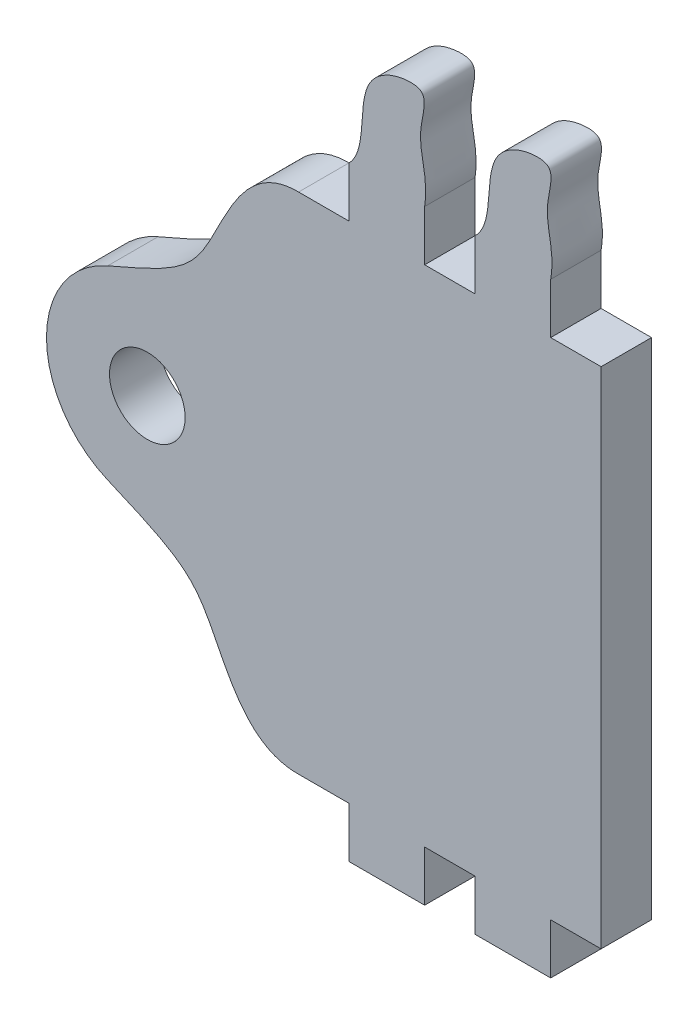
SolidWorks part; units mm, degrees
ref_plane "Front Plane" through (0, 0, 0) normal (0, 0, 1) x (1, 0, 0)
ref_plane "Top Plane" through (0, 0, 0) normal (0, 1, 0) x (1, 0, 0)
ref_plane "Right Plane" through (0, 0, 0) normal (1, 0, 0) x (0, 0, -1)
sketch "Sketch1" plane through (0, 0, 0) normal (0, 0, 1) x (1, 0, 0)
  line L0 (0, 0) -> (-3.2347, 0)
  line L1 (9.525, -15.875) -> (-9.525, -15.875)
  line L2 (9.525, -15.875) -> (9.525, 15.875)
  line L3 (9.525, 15.875) -> (-9.525, 15.875)
  line L4 (-9.525, -15.875) -> (-9.525, 15.875)
  line L5 (9.525, -15.875) -> (-9.525, 15.875) construction
  line L6 (9.525, 15.875) -> (-9.525, -15.875) construction
  line L7 (6.35, -15.875) -> (6.35, -19.05)
  line L8 (-6.35, 15.875) -> (-1.5875, 15.875)
  line L9 (-6.35, 15.875) -> (-6.35, 19.05)
  line L10 (-6.35, 19.05) -> (-1.5875, 19.05)
  line L11 (-1.5875, 15.875) -> (-1.5875, 19.05)
  line L12 (1.5875, 15.875) -> (6.35, 15.875)
  line L13 (1.5875, 15.875) -> (1.5875, 19.05)
  line L14 (1.5875, 19.05) -> (6.35, 19.05)
  line L15 (6.35, 15.875) -> (6.35, 19.05)
  line L16 (1.5875, -15.875) -> (1.5875, -19.05)
  line L17 (1.5875, -19.05) -> (6.35, -19.05)
  line L18 (-6.35, -15.875) -> (-6.35, -19.05)
  line L19 (-6.35, -19.05) -> (-1.5875, -19.05)
  line L20 (-1.5875, -15.875) -> (-1.5875, -19.05)
  circle A0 centre (-19.05, 0) radius 2.3813
  circle A1 centre (-19.05, 0) radius 6.35
  spline S0 degree 3 poles (-21.5476, 5.8382) (-17.7414, 7.4665) (-15.0309, 8.8365) (-13.0093, 15.9171) (-9.525, 15.875) knots 0 0 0 0 0.458191 1 1 1 1
  spline S1 degree 3 poles (-6.35, 19.05) (-5.1089, 20.3128) (-6.2488, 23.7826) (-3.5047, 25.4227) (-1.2706, 25.4019) (-2.3305, 22.1182) (-1.303, 20.9023) (-1.5875, 19.05) knots 0 0 0 0 0.348301 0.511854 0.587996 0.709542 1 1 1 1
  spline S2 degree 3 poles (1.5875, 19.05) (2.8761, 20.283) (1.7509, 23.717) (4.4801, 25.3439) (6.714, 25.3233) (5.6646, 22.0756) (6.6616, 20.8588) (6.35, 19.05) knots 0 0 0 0 0.347504 0.512636 0.589513 0.712232 1 1 1 1
  spline S3 degree 3 poles (-21.5476, -5.8382) (-17.7414, -7.4665) (-15.0309, -8.8365) (-13.0093, -15.9171) (-9.525, -15.875) knots 0 0 0 0 0.458191 1 1 1 1
  point P0 (0, 0)
  dimension "D3" = 4.7625
  dimension "D4" = 9.525
  dimension "D5" = 12.7
  dimension "D1" = 19.05
  dimension "D2" = 31.75
  dimension "D6" = 4.7625
  dimension "D7" = 4.7625
  dimension "D8" = 3.175
  dimension "D9" = 3.175
  dimension "D10" = 3.175
  dimension "D11" = 3.175
extrude "Boss-Extrude1" add sketch "Sketch1" along normal blind 3.175
